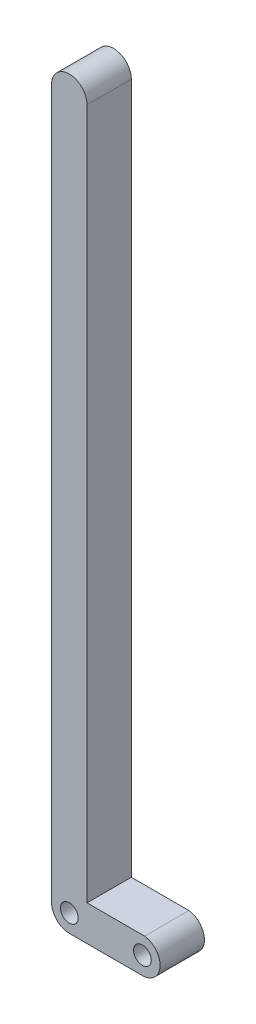
SolidWorks part; units mm, degrees
ref_plane "前视基准面" through (0, 0, 0) normal (0, 0, 1) x (1, 0, 0)
ref_plane "上视基准面" through (0, 0, 0) normal (0, 1, 0) x (1, 0, 0)
ref_plane "右视基准面" through (0, 0, 0) normal (1, 0, 0) x (0, 0, -1)
other "Configuration Table"
sketch "草图1" plane through (0, 0, 0) normal (0, 0, 1) x (1, 0, 0)
  line L0 (0, 0) -> (8.25, 0) construction
  line L1 (0, 0) -> (0, 80) construction
  line L2 (-2, 80) -> (-2, 0)
  line L3 (1.9999, 1.9843) -> (1.9999, 79.9843)
  line L4 (1.9999, 1.9843) -> (8.4999, 1.9843)
  line L5 (0, -2) -> (8.25, -2)
  arc A0 (-2, 0) -> (0, -2) centre (0, 0) ccw
  arc A1 (8.25, -2) -> (8.4999, 1.9843) centre (8.25, 0) ccw
  arc A2 (1.9999, 79.9843) -> (-2, 80) centre (0, 80) ccw
  circle A3 centre (0, 0) radius 1
  circle A4 centre (8.25, 0) radius 1
  dimension "D1" = 4
  dimension "D3" = 4
  dimension "D5" = 4
  dimension "D8" = 2
  dimension "D9" = 2
  dimension "D2" = 8.25
  dimension "D4" = 80
  dimension "D6" = 78
  dimension "D7" = 6.5
extrude "凸台-拉伸1" add sketch "草图1" along normal blind 5
